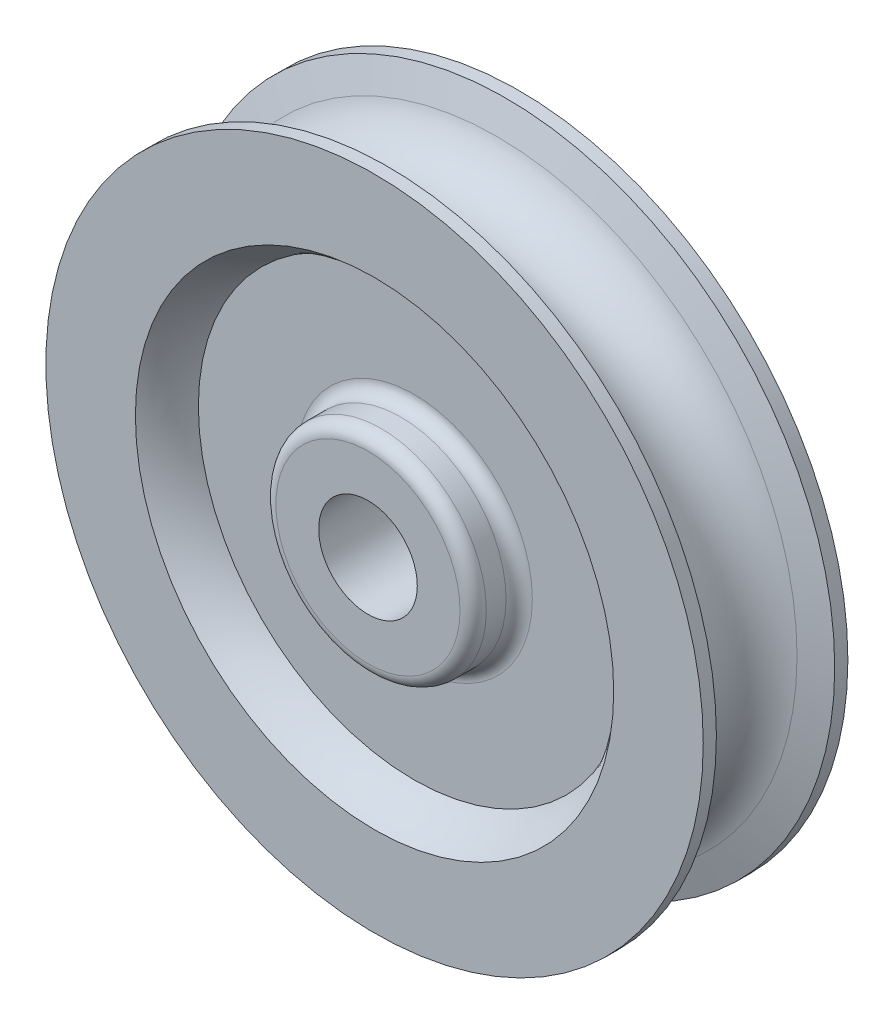
SolidWorks part; units mm, degrees
ref_plane "Front Plane" through (0, 0, 0) normal (0, 0, 1) x (1, 0, 0)
ref_plane "Top Plane" through (0, 0, 0) normal (0, 1, 0) x (1, 0, 0)
ref_plane "Right Plane" through (0, 0, 0) normal (1, 0, 0) x (0, 0, -1)
sketch "Sketch1" plane through (0, 0, 0) normal (0, 1, 0) x (1, 0, 0)
  line L0 (0, 0) -> (0, 12)
  line L4 (50, 3) -> (50, 1)
  line L5 (50, 1) -> (36.381, 1)
  line L6 (50, 3) -> (45.6241, 4.3609)
  line L7 (7.5, 0) -> (7.5, 12)
  line L8 (18, 7) -> (32.8013, 7)
  line L11 (7.5, 0) -> (14, 0)
  line L12 (16, 2) -> (16, 5)
  line L13 (16, 22) -> (16, 19)
  line L14 (7.5, 24) -> (14, 24)
  line L15 (18, 17) -> (32.8013, 17)
  line L16 (7.5, 24) -> (7.5, 12)
  line L17 (50, 21) -> (45.6241, 19.6391)
  line L18 (50, 23) -> (36.381, 23)
  line L19 (50, 21) -> (50, 23)
  arc A0 (45.6241, 19.6391) -> (45.6241, 4.3609) centre (48, 12) ccw
  arc A1 (32.8013, 7) -> (36.381, 1) centre (48, 12) ccw
  arc A2 (14, 0) -> (16, 2) centre (14, 2) ccw
  arc A3 (16, 5) -> (18, 7) centre (18, 5) cw
  arc A4 (16, 19) -> (18, 17) centre (18, 19) ccw
  arc A5 (14, 24) -> (16, 22) centre (14, 22) cw
  arc A6 (32.8013, 17) -> (36.381, 23) centre (48, 12) cw
  dimension "D1" = 7.5
  dimension "D3" = 2
  dimension "D4" = 2
revolve "Revolve1" add sketch "Sketch1" angle 360 about L0
